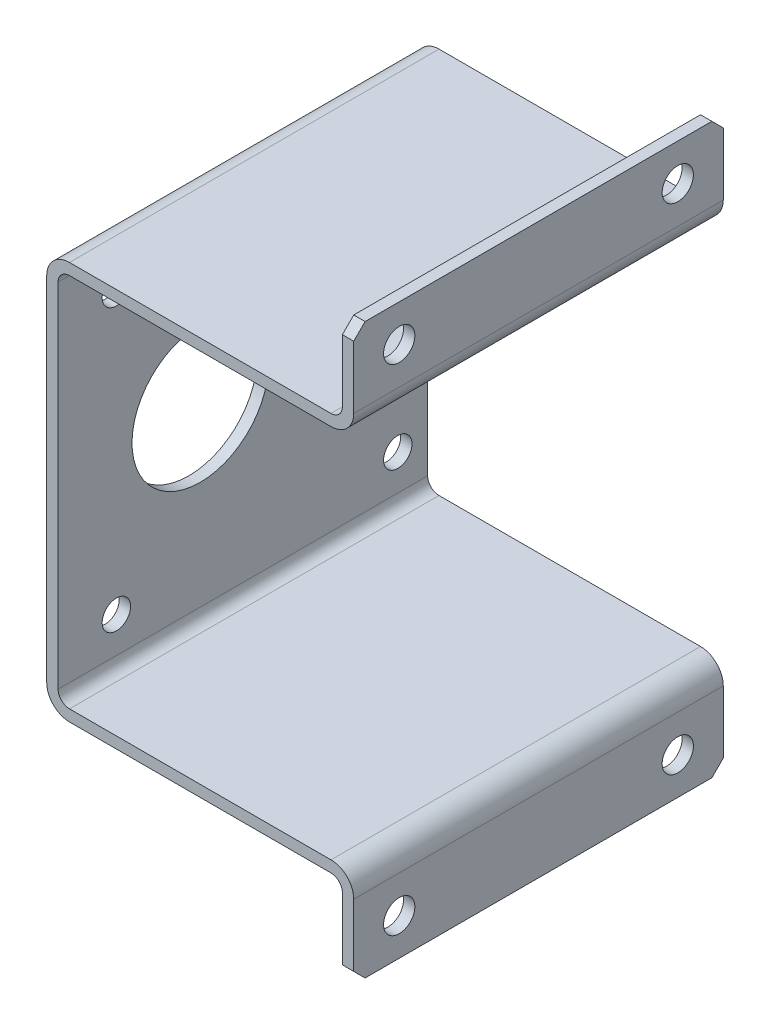
SolidWorks part; units mm, degrees
ref_plane "Front" through (0, 0, 0) normal (0, 0, 1) x (1, 0, 0)
ref_plane "Top" through (0, 0, 0) normal (0, 1, 0) x (1, 0, 0)
ref_plane "Right" through (0, 0, 0) normal (1, 0, 0) x (0, 0, -1)
sketch "Sketch1" plane through (0, 0, 0) normal (0, 0, 1) x (1, 0, 0)
  line L0 (0, -33) -> (0, -50)
  line L1 (0, -50) -> (-2, -50)
  line L2 (-2, -50) -> (-2, -35)
  line L3 (-2, -35) -> (-54, -35)
  line L4 (-54, -35) -> (-54, 35)
  line L5 (-54, 35) -> (-2, 35)
  line L6 (-2, 35) -> (-2, 50)
  line L7 (-2, 50) -> (0, 50)
  line L8 (0, 50) -> (0, 33)
  line L9 (0, 33) -> (-52, 33)
  line L10 (-52, 33) -> (-52, -33)
  line L11 (-52, -33) -> (0, -33)
  line L12 (0, 0) -> (-57.2473, 0) construction
  dimension "D1" = 2
  dimension "D2" = 2
  dimension "D3" = 2
  dimension "D4" = 100
  dimension "D5" = 70
  dimension "D6" = 54
extrude "Boss-Extrude1" add sketch "Sketch1" along normal blind 65
sketch "Sketch2" plane through (-54, 0, 0) normal (-1, 0, 0) x (0, 0, 1)
  line L0 (0, 35) -> (0, -35) construction
  circle A0 centre (40, 0) radius 12
  dimension "D1" = 24
  dimension "D2" = 40
extrude "Cut-Extrude1" cut sketch "Sketch2" against normal through all
hole_wizard "Ø5.5 (5.5) Diameter Hole1" positions "Sketch4" profile "Sketch3" hole size "Ø5.5" standard "ISO" end condition through all
sketch "Sketch4" plane through (-2, 0, 0) normal (-1, 0, 0) x (0, 0, 1)
  line L0 (0, 0) -> (65, 0) construction
  line L1 (65, 35) -> (65, -35) construction
  line L3 (0, 35) -> (0, -35) construction
  point P0 (57, -43.5)
  point P1 (8, -43.5)
  point P3 (57, 43.5)
  point P5 (8, 43.5)
  dimension "D1" = 87
  dimension "D2" = 8
  dimension "D3" = 49
sketch "Sketch3" plane through (-2, -43.5, 57) normal (0, 1, 0) x (0, 0, 1)
  line L0 (0, 0) -> (0, 2)
  line L1 (0, 2) -> (2.75, 2)
  line L2 (2.75, 2) -> (2.75, 0)
  line L5 (2.75, 0) -> (0, 0)
  line L11 (0, -6.35) -> (0, 107.95) construction
  dimension "Thru Hole Dia." = 5.5
  dimension "Thru Hole Depth" = 2
hole_wizard "Ø5.0 (5) Diameter Hole1" positions "Sketch6" profile "Sketch5" hole size "Ø5.0" standard "ISO" end condition through all
sketch "Sketch6" plane through (-54, 0, 0) normal (-1, 0, 0) x (0, 0, 1)
  line L0 (0, 35) -> (0, -35) construction
  line L1 (0, 0) -> (71.6959, 0) construction
  line L3 (30, 0) -> (54.7487, 24.7487) construction
  line L5 (30, 0) -> (30, 35) construction
  circle A0 centre (30, 0) radius 35 construction
  point P0 (54.7487, 24.7487)
  point P1 (54.7487, -24.7487)
  point P3 (5.2513, -24.7487)
  point P5 (5.2513, 24.7487)
  dimension "D1" = 70
  dimension "D2" = 30
  dimension "D3" = 45
sketch "Sketch5" plane through (-54, 24.7487, 54.7487) normal (0, 1, 0) x (0, 0, 1)
  line L0 (0, 0) -> (0, 54)
  line L1 (0, 54) -> (2.5, 54)
  line L2 (2.5, 54) -> (2.5, 0)
  line L5 (2.5, 0) -> (0, 0)
  line L11 (0, -6.35) -> (0, 107.95) construction
  dimension "Thru Hole Dia." = 5
  dimension "Thru Hole Depth" = 54
chamfer "Chamfer1" distance 2 angle 45 4 edges at (-1, 50, 0) (-1, 50, 65) (-1, -50, 0) (-1, -50, 65)
fillet "Fillet1" radius 4 4 edges at (-54, 35, 32.5) (-54, -35, 32.5) (0, 33, 32.5) (0, -33, 32.5)
fillet "Fillet2" radius 2 4 edges at (-2, 35, 32.5) (-2, -35, 32.5) (-52, -33, 32.5) (-52, 33, 32.5)
